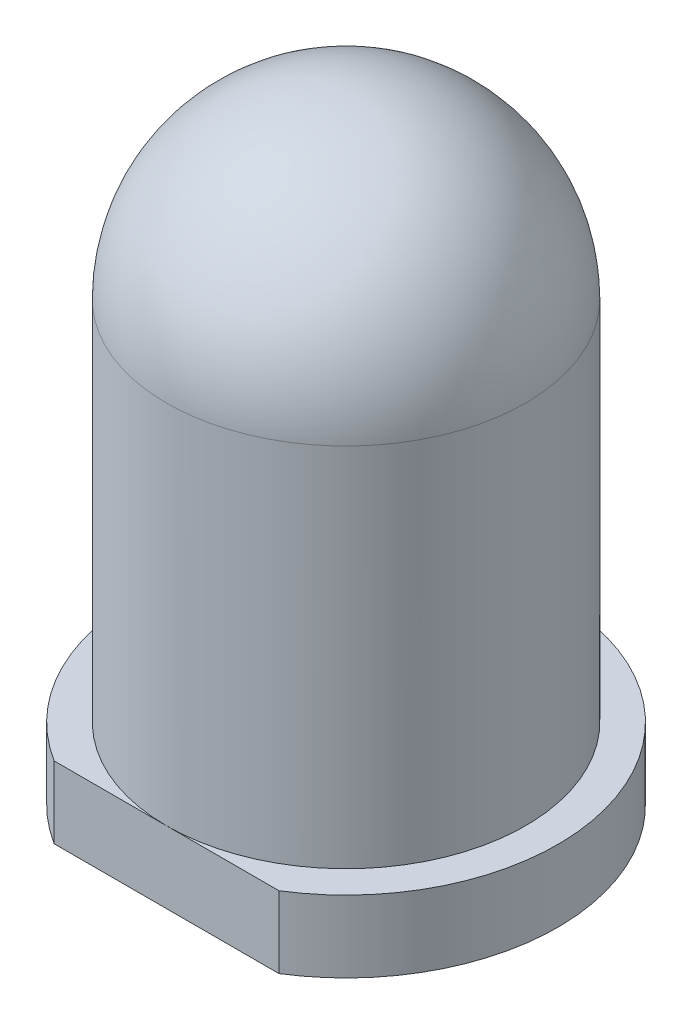
SolidWorks part; units mm, degrees
material "ABS PC"
ref_plane "Front Plane" through (0, 0, 0) normal (0, 0, 1) x (1, 0, 0)
ref_plane "Top Plane" through (0, 0, 0) normal (0, 1, 0) x (1, 0, 0)
ref_plane "Right Plane" through (0, 0, 0) normal (1, 0, 0) x (0, 0, -1)
sketch "Sketch1" plane through (0, 0, 0) normal (0, 1, 0) x (1, 0, 0)
  circle A0 centre (0, 0) radius 2.5
  dimension "D1" = 5
extrude "Base" add sketch "Sketch1" along normal blind 8.6
fillet "Dome" radius 2.5 1 edges at (0, 8.6, 2.5)
sketch "BaseCutSketch" plane through (0, 0, 0) normal (0, 1, 0) x (1, 0, 0)
  line L0 (1.566, -2.5) -> (-1.566, -2.5)
  arc A0 (1.566, -2.5) -> (-1.566, -2.5) centre (0, 0) ccw
  circle A2 centre (0, 0) radius 2.5 construction
  dimension "D1" = 5.9
extrude "BaseCut" add sketch "BaseCutSketch" along normal blind 1
